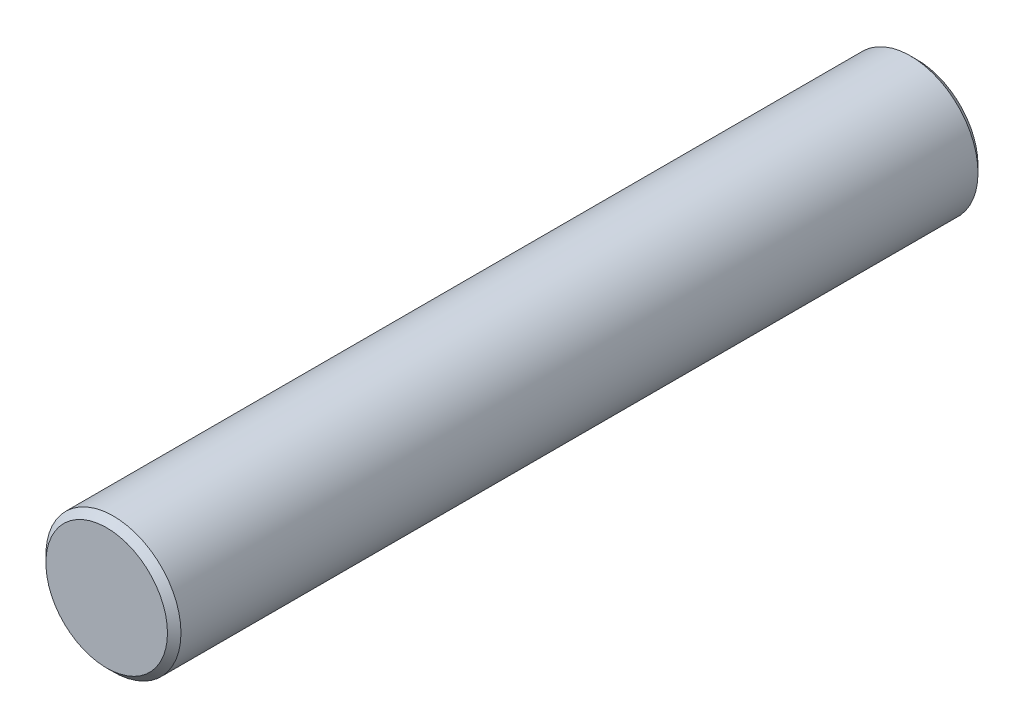
SolidWorks part; units mm, degrees
ref_plane "Front Plane" through (0, 0, 0) normal (0, 0, 1) x (1, 0, 0)
ref_plane "Top Plane" through (0, 0, 0) normal (0, 1, 0) x (1, 0, 0)
ref_plane "Right Plane" through (0, 0, 0) normal (1, 0, 0) x (0, 0, -1)
sketch "Sketch1" plane through (0, 0, 0) normal (0, 0, 1) x (1, 0, 0)
  circle A0 centre (0, 0) radius 1
extrude "Boss-Extrude1" add sketch "Sketch1" along normal mid plane 12
chamfer "Chamfer1" distance 0.1 angle 45 2 edges at (1, 0, -6) (1, 0, 6)
